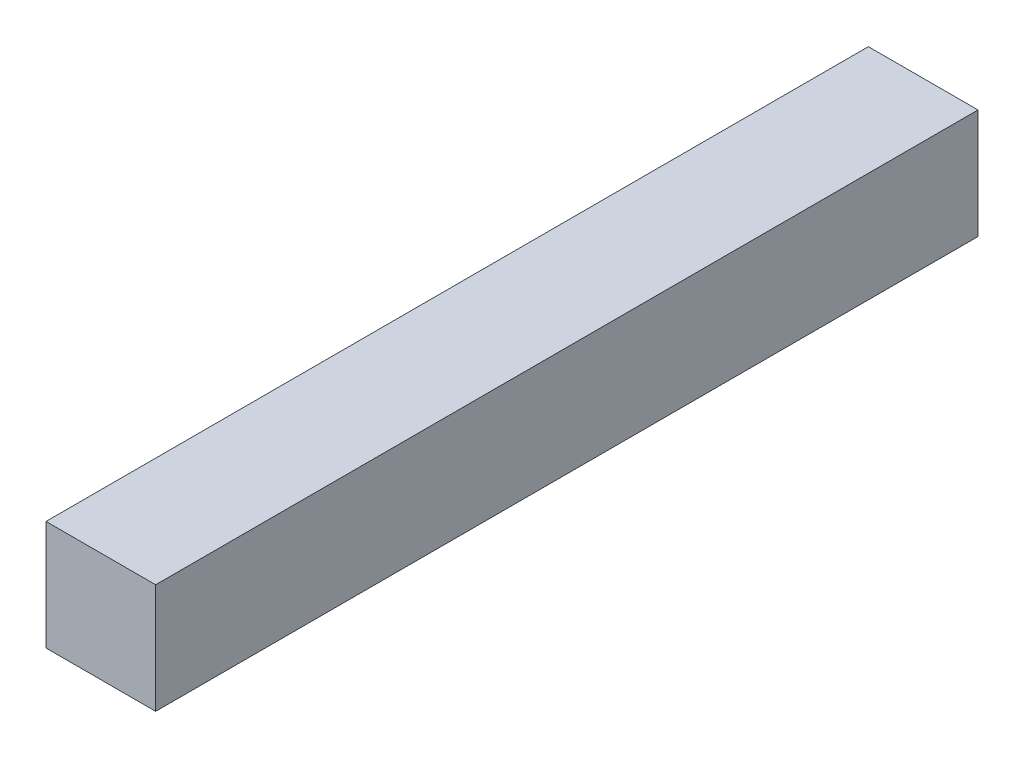
SolidWorks part; units mm, degrees
ref_plane "Alzado" through (0, 0, 0) normal (0, 0, 1) x (1, 0, 0)
ref_plane "Planta" through (0, 0, 0) normal (0, 1, 0) x (1, 0, 0)
ref_plane "Vista lateral" through (0, 0, 0) normal (1, 0, 0) x (0, 0, -1)
sketch "Croquis1" plane through (0, 0, 0) normal (0, 0, 1) x (1, 0, 0)
  line L1 (-10, -10) -> (10, -10)
  line L2 (-10, -10) -> (-10, 10)
  line L3 (-10, 10) -> (10, 10)
  line L4 (10, -10) -> (10, 10)
  line L5 (-10, -10) -> (10, 10) construction
  line L6 (-10, 10) -> (10, -10) construction
  point P0 (0, 0)
  dimension "D1" = 20
  dimension "D2" = 20
extrude "Saliente-Extruir1" add sketch "Croquis1" along normal mid plane 150
sketch "Croquis2" plane through (0, 0, -75) normal (0, 0, -1) x (-1, 0, 0)
  line L0 (0, 10) -> (0, -10) construction
  line L1 (-10, 10) -> (10, 10) construction
  line L2 (10, -10) -> (-10, -10) construction
  line L3 (-10, 0) -> (10, 0) construction
  line L4 (-10, -10) -> (-10, 10) construction
  line L5 (10, 10) -> (10, -10) construction
  circle A0 centre (0, 0) radius 2.5
  dimension "D1" = 5
extrude "Cortar-Extruir2" cut sketch "Croquis2" against normal blind 10
